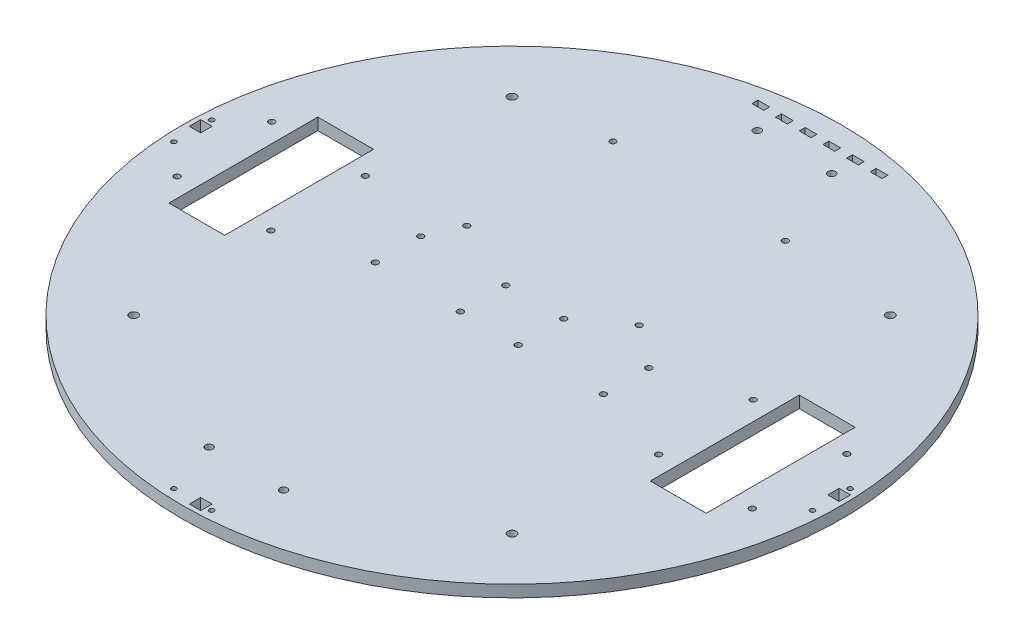
SolidWorks part; units mm, degrees
ref_plane "Front Plane" through (0, 0, 0) normal (0, 0, 1) x (1, 0, 0)
ref_plane "Top Plane" through (0, 0, 0) normal (0, 1, 0) x (1, 0, 0)
ref_plane "Right Plane" through (0, 0, 0) normal (1, 0, 0) x (0, 0, -1)
sketch "Sketch1" plane through (0, 0, 0) normal (0, 1, 0) x (1, 0, 0)
  line L0 (168.375, 7.335) -> (174.525, 7.335)
  line L1 (-144.3, 40) -> (-114.3, 40)
  line L2 (-144.3, 40) -> (-144.3, -40)
  line L3 (-144.3, -40) -> (-114.3, -40)
  line L4 (-114.3, 40) -> (-114.3, -40)
  line L13 (114.3, 40) -> (144.3, 40)
  line L14 (114.3, 40) -> (114.3, -40)
  line L15 (114.3, -40) -> (144.3, -40)
  line L16 (144.3, 40) -> (144.3, -40)
  line L17 (1.185, -168.375) -> (7.335, -168.375)
  line L18 (1.185, -168.375) -> (1.185, -174.525)
  line L19 (1.185, -174.525) -> (7.335, -174.525)
  line L20 (7.335, -168.375) -> (7.335, -174.525)
  line L21 (168.375, 7.335) -> (168.375, 1.185)
  line L22 (168.375, 1.185) -> (174.525, 1.185)
  line L23 (174.525, 7.335) -> (174.525, 1.185)
  line L24 (-174.525, 7.335) -> (-168.375, 7.335)
  line L25 (-174.525, 7.335) -> (-174.525, 1.185)
  line L26 (-174.525, 1.185) -> (-168.375, 1.185)
  line L27 (-168.375, 7.335) -> (-168.375, 1.185)
  line L28 (-21.295, 162.8645) -> (-14.945, 162.8645)
  line L29 (-33.995, 166.0395) -> (-27.645, 166.0395)
  line L30 (-33.995, 166.0395) -> (-33.995, 162.8645)
  line L31 (-33.995, 162.8645) -> (-27.645, 162.8645)
  line L32 (-27.645, 166.0395) -> (-27.645, 162.8645)
  line L33 (-14.945, 166.0395) -> (-14.945, 162.8645)
  line L34 (-21.295, 166.0395) -> (-14.945, 166.0395)
  line L35 (-21.295, 166.0395) -> (-21.295, 162.8645)
  line L36 (-8.595, 162.8645) -> (-2.245, 162.8645)
  line L37 (-2.245, 166.0395) -> (-2.245, 162.8645)
  line L38 (-8.595, 166.0395) -> (-2.245, 166.0395)
  line L39 (-8.595, 166.0395) -> (-8.595, 162.8645)
  line L40 (4.105, 162.8645) -> (10.455, 162.8645)
  line L41 (10.455, 166.0395) -> (10.455, 162.8645)
  line L42 (4.105, 166.0395) -> (10.455, 166.0395)
  line L43 (4.105, 166.0395) -> (4.105, 162.8645)
  line L44 (16.805, 162.8645) -> (23.155, 162.8645)
  line L45 (23.155, 166.0395) -> (23.155, 162.8645)
  line L46 (16.805, 166.0395) -> (23.155, 166.0395)
  line L47 (16.805, 166.0395) -> (16.805, 162.8645)
  line L48 (29.505, 162.8645) -> (35.855, 162.8645)
  line L49 (35.855, 166.0395) -> (35.855, 162.8645)
  line L50 (29.505, 166.0395) -> (35.855, 166.0395)
  line L51 (29.505, 166.0395) -> (29.505, 162.8645)
  circle A0 centre (0, 0) radius 177
  circle A1 centre (-154.46, 25.4) radius 1.6
  circle A2 centre (-154.46, -25.4) radius 1.6
  circle A3 centre (154.46, 25.4) radius 1.6
  circle A4 centre (154.46, -25.4) radius 1.6
  circle A5 centre (-104.14, 25.4) radius 1.6
  circle A6 centre (-104.14, -25.4) radius 1.6
  circle A7 centre (104.14, 25.4) radius 1.6
  circle A8 centre (104.14, -25.4) radius 1.6
  circle A9 centre (-53.7, 107.95) radius 1.6
  circle A10 centre (38.8, 107.95) radius 1.6
  circle A11 centre (-53.7, 29.45) radius 1.6
  circle A12 centre (38.8, 29.45) radius 1.6
  circle A13 centre (-101.6, -101.6) radius 2.2479
  circle A14 centre (101.6, -101.6) radius 2.2479
  circle A15 centre (-101.6, 101.6) radius 2.2479
  circle A16 centre (101.6, 101.6) radius 2.2479
  circle A17 centre (-20, -142.687) radius 2
  circle A18 centre (20, -142.687) radius 2
  circle A19 centre (-20, 151.7193) radius 2
  circle A20 centre (20, 151.7193) radius 2
  circle A21 centre (-10.125, -171.45) radius 1.3
  circle A22 centre (10.125, -171.45) radius 1.3
  circle A23 centre (171.45, -10.125) radius 1.3
  circle A24 centre (171.45, 10.125) radius 1.3
  circle A25 centre (-171.45, -10.125) radius 1.3
  circle A26 centre (-171.45, 10.125) radius 1.3
  circle A27 centre (-61.26, 12.194) radius 1.6
  circle A28 centre (-61.26, -12.19) radius 1.6
  circle A29 centre (-15.54, 12.194) radius 1.6
  circle A30 centre (-15.54, -12.19) radius 1.6
  circle A31 centre (61.26, -12.19) radius 1.6
  circle A32 centre (15.54, -12.19) radius 1.6
  circle A33 centre (15.54, 12.194) radius 1.6
  circle A34 centre (61.26, 12.194) radius 1.6
  point P9 (-114.3, 0)
  point P10 (-0.9618, 0)
  point P11 (-0.9618, 0)
  point P14 (114.3, 0)
  point P26 (-144.3, 0)
  point P27 (144.3, 0)
  point P109 (-50.1296, -41.1474)
  point P112 (-21.295, -30.7086)
  point P115 (-21.295, -41.1474)
  point P116 (-54.7999, -40.696)
  point P117 (-11.2929, -19.5354)
  point P118 (-23.4371, -13.4147)
  point P125 (25.9706, -34.6504)
  point P126 (0, 0)
  point P127 (24.6707, -12.19)
  point P128 (33.9869, -12.19)
  point P131 (0, 0)
  point P132 (74.5019, -12.19)
  dimension "D1" = 354
  dimension "D10" = 3.2
  dimension "D12" = 10.16
  dimension "D13" = 3.2
  dimension "D16" = 10.16
  dimension "D17" = 50.8
  dimension "D20" = 3.2
  dimension "D22" = 3.2
  dimension "D23" = 10.16
  dimension "D24" = 50.8
  dimension "D25" = 25.4
  dimension "D26" = 3.2
  dimension "D27" = 3.2
  dimension "D32" = 3.2
  dimension "D33" = 3.2
  dimension "D34" = 3.2
  dimension "D35" = 3.2
  dimension "D44" = 4.4958
  dimension "D45" = 4.4958
  dimension "D46" = 4.4958
  dimension "D47" = 4.4958
  dimension "D55" = 4
  dimension "D56" = 4
  dimension "D59" = 20
  dimension "D60" = 4
  dimension "D61" = 4
  dimension "D62" = 0
  dimension "D63" = 40
  dimension "D64" = 20
  dimension "D65" = 2.6
  dimension "D66" = 2.6
  dimension "D74" = 171.45
  dimension "D75" = 2.6
  dimension "D76" = 2.6
  dimension "D77" = 0
  dimension "D87" = 2.6
  dimension "D88" = 2.6
  dimension "D90" = 2.79
  dimension "D92" = 0
  dimension "D98" = 3.2
  dimension "D99" = 3.2
  dimension "D100" = 3.2
  dimension "D101" = 3.2
  dimension "D102" = 24.384
  dimension "D103" = 24.384
  dimension "D104" = 45.72
  dimension "D105" = 45.72
  dimension "D106" = 0
  dimension "D110" = 3.2
  dimension "D111" = 3.2
  dimension "D112" = 3.2
  dimension "D113" = 3.2
  dimension "D115" = 45.72
  dimension "D117" = 24.384
  dimension "D119" = 24.384
  dimension "D122" = 3.2
  dimension "D123" = 3.2
  dimension "D2" = 30
  dimension "D3" = 80
  dimension "D4" = 0
  dimension "D5" = 114.3
  dimension "D6" = 30
  dimension "D7" = 80
  dimension "D8" = 0
  dimension "D9" = 114.3
  dimension "D11" = 50.8
  dimension "D14" = 10.16
  dimension "D15" = 25.4
  dimension "D18" = 25.4
  dimension "D19" = 10.16
  dimension "D21" = 10.16
  dimension "D28" = 50.8
  dimension "D29" = 10.16
  dimension "D30" = 10.16
  dimension "D31" = 25.4
  dimension "D36" = 78.5
  dimension "D37" = 78.5
  dimension "D38" = 92.5
  dimension "D39" = 92.5
  dimension "D40" = 0
  dimension "D41" = 0
  dimension "D42" = 38.8
  dimension "D43" = 107.95
  dimension "D48" = 203.2
  dimension "D49" = 203.2
  dimension "D50" = 203.2
  dimension "D51" = 203.2
  dimension "D52" = 0
  dimension "D53" = 101.6
  dimension "D54" = 101.6
  dimension "D57" = 40
  dimension "D58" = 0
  dimension "D67" = 0
  dimension "D68" = 20.25
  dimension "D69" = 10.125
  dimension "D70" = 6.15
  dimension "D71" = 6.15
  dimension "D72" = 2.79
  dimension "D73" = 3.075
  dimension "D78" = 20.25
  dimension "D79" = 10.125
  dimension "D80" = 6.15
  dimension "D81" = 6.15
  dimension "D82" = 2.79
  dimension "D83" = 3.075
  dimension "D84" = 171.45
  dimension "D85" = 6.15
  dimension "D86" = 6.15
  dimension "D89" = 20.25
  dimension "D91" = 3.075
  dimension "D93" = 171.45
  dimension "D94" = 10.125
  dimension "D95" = 3.175
  dimension "D96" = 6.35
  dimension "D107" = 0
  dimension "D108" = 53.04
  dimension "D109" = 27.81
  dimension "D114" = 0
  dimension "D116" = 0
  dimension "D118" = 45.72
  dimension "D120" = 53.04
  dimension "D121" = 27.81
  dimension "D97" = 6
extrude "Boss-Extrude1" add sketch "Sketch1" along normal blind 6.35
